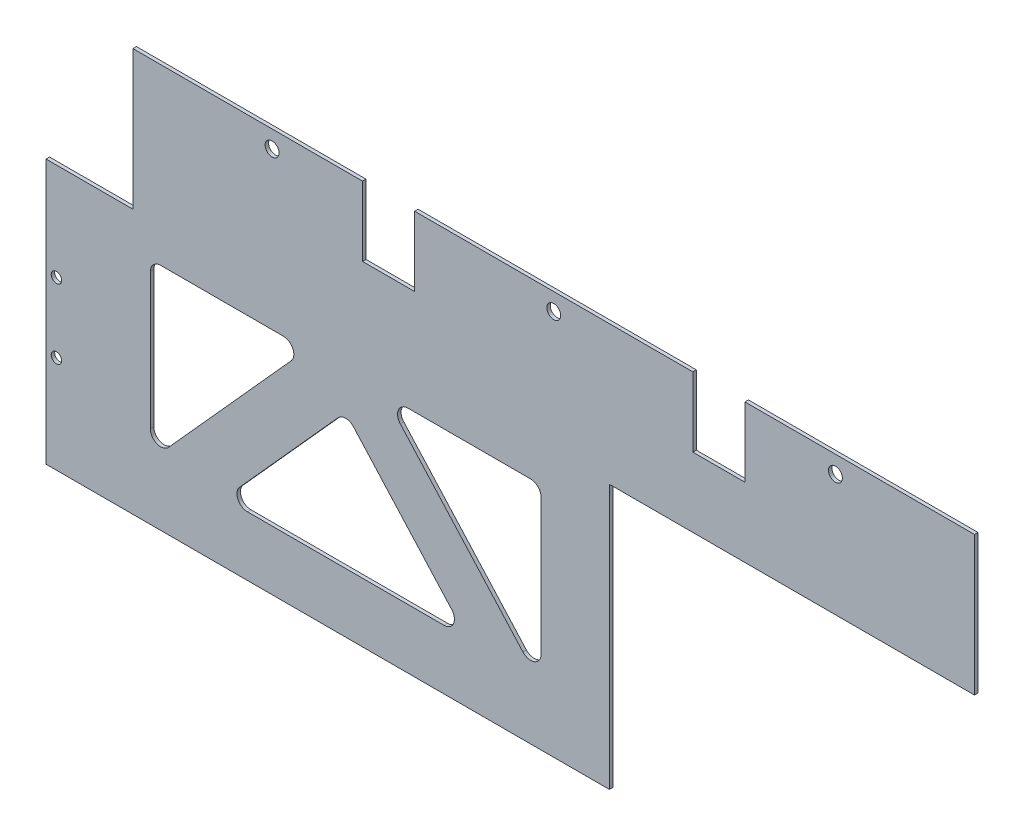
SolidWorks part; units mm, degrees
material "Thornel Mat VMA"
ref_plane "前视基准面" through (0, 0, 0) normal (0, 0, 1) x (1, 0, 0)
ref_plane "上视基准面" through (0, 0, 0) normal (0, 1, 0) x (1, 0, 0)
ref_plane "右视基准面" through (0, 0, 0) normal (1, 0, 0) x (0, 0, -1)
sketch "草图1" plane through (0, 0, 0) normal (0, 0, 1) x (1, 0, 0)
  line L0 (0, 0) -> (0, 76)
  line L1 (0, 76) -> (25, 76)
  line L2 (25, 76) -> (25, 116)
  line L3 (25, 116) -> (267, 116)
  line L4 (267, 116) -> (267, 76)
  line L5 (267, 76) -> (292, 76)
  line L6 (292, 76) -> (292, 0)
  line L7 (292, 0) -> (0, 0)
  line L8 (3, 48) -> (3, 28) construction
  line L9 (0, 38) -> (292, 38) construction
  line L10 (146, 116) -> (146, 0) construction
  line L11 (289, 48) -> (289, 28) construction
  circle A0 centre (3, 48) radius 1.5
  circle A1 centre (3, 28) radius 1.5
  circle A2 centre (289, 28) radius 1.5
  circle A3 centre (289, 48) radius 1.5
  point P13 (3, 38)
  dimension "D7" = 3
  dimension "D1" = 292
  dimension "D2" = 76
  dimension "D3" = 40
  dimension "D4" = 25
  dimension "D5" = 20
  dimension "D6" = 3
extrude "凸台-拉伸1" add sketch "草图1" along normal blind 1
sketch "草图2" plane through (0, 0, 1) normal (0, 0, 1) x (1, 0, 0)
  line L0 (146, 116) -> (146, 0) construction
  line L1 (267, 116) -> (25, 116) construction
  line L2 (0, 0) -> (292, 0) construction
  line L3 (186, 116) -> (186, 96)
  line L4 (91, 116) -> (106, 116)
  line L5 (91, 116) -> (91, 96)
  line L6 (91, 96) -> (106, 96)
  line L7 (106, 116) -> (106, 96)
  line L8 (201, 96) -> (186, 96)
  line L9 (201, 116) -> (201, 96)
  line L10 (201, 116) -> (186, 116)
  line L11 (25, 116) -> (25, 76) construction
  circle A0 centre (65, 111) radius 2
  circle A1 centre (227, 111) radius 2
  circle A2 centre (146, 111) radius 2
  point P14 (98.5, 116)
  point P15 (193.5, 116)
  dimension "D4" = 4
  dimension "D7" = 4
  dimension "D1" = 95
  dimension "D2" = 15
  dimension "D3" = 20
  dimension "D5" = 5
  dimension "D6" = 40
extrude "切除-拉伸1" cut sketch "草图2" against normal through all
sketch "草图3" plane through (0, 0, 1) normal (0, 0, 1) x (1, 0, 0)
  line L0 (292, 76) -> (267, 76) construction
  line L1 (292, 0) -> (162, 0)
  line L2 (292, 0) -> (292, 76)
  line L3 (292, 76) -> (162, 76)
  line L4 (162, 0) -> (162, 76)
  line L5 (292, 0) -> (292, 76) construction
  dimension "D1" = 130
extrude "切除-拉伸2" cut sketch "草图3" against normal through all
sketch "草图4" plane through (0, 0, 1) normal (0, 0, 1) x (1, 0, 0)
  line L0 (86.1804, 56) -> (51.1804, 17.1111)
  line L1 (51.1804, 17.1111) -> (121.1804, 17.1111)
  line L2 (86.1804, 56) -> (121.1804, 17.1111)
  line L3 (30, 66) -> (30, 16)
  line L4 (30, 16) -> (75, 66)
  line L5 (75, 66) -> (30, 66)
  line L6 (91, 116) -> (25, 116) construction
  line L7 (0, 76) -> (0, 0) construction
  line L8 (86.1804, 56) -> (86.1804, 17.1111) construction
  line L9 (142.3609, 16) -> (97.3609, 66)
  line L10 (142.3609, 66) -> (142.3609, 16)
  line L11 (97.3609, 66) -> (142.3609, 66)
  dimension "D1" = 60
  dimension "D2" = 50
  dimension "D3" = 50
  dimension "D4" = 45
  dimension "D5" = 30
  dimension "D6" = 15
  dimension "D7" = 70
extrude "切除-拉伸3" cut sketch "草图4" against normal up to next contours L4 L5 L3 | L8 L0 L1 | L2 L8 L1 | L11 L9 L10
fillet "圆角1" radius 3 9 edges at (142.3609, 16, 0.5) (97.3609, 66, 0.5) (142.3609, 66, 0.5) (121.1804, 17.1111, 0.5) (51.1804, 17.1111, 0.5) (86.1804, 56, 0.5) (30, 16, 0.5) (75, 66, 0.5) (30, 66, 0.5)
